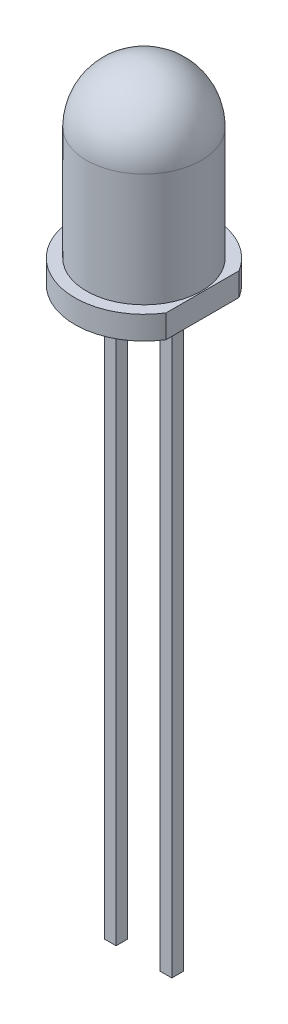
SolidWorks part; units mm, degrees
ref_plane "Front Plane" through (0, 0, 0) normal (0, 0, 1) x (1, 0, 0)
ref_plane "Top Plane" through (0, 0, 0) normal (0, 1, 0) x (1, 0, 0)
ref_plane "Right Plane" through (0, 0, 0) normal (1, 0, 0) x (0, 0, -1)
sketch "Sketch1" plane through (0, 0, 0) normal (0, 1, 0) x (1, 0, 0)
  line L0 (2.525, -1.5732) -> (2.525, 1.5732)
  line L1 (-2.975, 0) -> (2.525, 0) construction
  arc A1 (2.525, 1.5732) -> (2.525, -1.5732) centre (0, 0) ccw
  point P1 (-2.975, 0)
  dimension "D1" = 2.975
  dimension "D2" = 5.5
extrude "Boss-Extrude1" add sketch "Sketch1" along normal blind 1
sketch "Sketch4" plane through (0, 0, 0) normal (0, 0, 1) x (1, 0, 0)
  line L0 (0, 0) -> (0, 8.35) construction
  line L1 (-2.475, 1) -> (-2.475, 5.875)
  line L2 (-2.475, 1) -> (0, 1)
  line L3 (0, 1) -> (0, 8.35)
  line L4 (2.525, 1) -> (-2.975, 1) construction
  arc A0 (-2.475, 5.875) -> (0, 8.35) centre (0, 5.875) cw
  dimension "D1" = 8.35
  dimension "D2" = 0.5
revolve "Revolve1" add sketch "Sketch4" angle 360 about L0
sketch "Sketch5" plane through (0, 0, 0) normal (0, -1, 0) x (-1, 0, 0)
  line L0 (0.95, 0) -> (-0.95, 0) construction
  line L1 (-0.95, -0.25) -> (-1.45, -0.25)
  line L2 (-0.95, -0.25) -> (-0.95, 0.25)
  line L3 (-0.95, 0.25) -> (-1.45, 0.25)
  line L4 (-1.45, -0.25) -> (-1.45, 0.25)
  line L5 (1.45, -0.25) -> (0.95, -0.25)
  line L6 (1.45, -0.25) -> (1.45, 0.25)
  line L7 (1.45, 0.25) -> (0.95, 0.25)
  line L8 (0.95, -0.25) -> (0.95, 0.25)
  point P10 (0, 0)
  dimension "D1" = 1.9
  dimension "D2" = 0.5
extrude "Boss-Extrude2" add sketch "Sketch5" along normal blind 25
